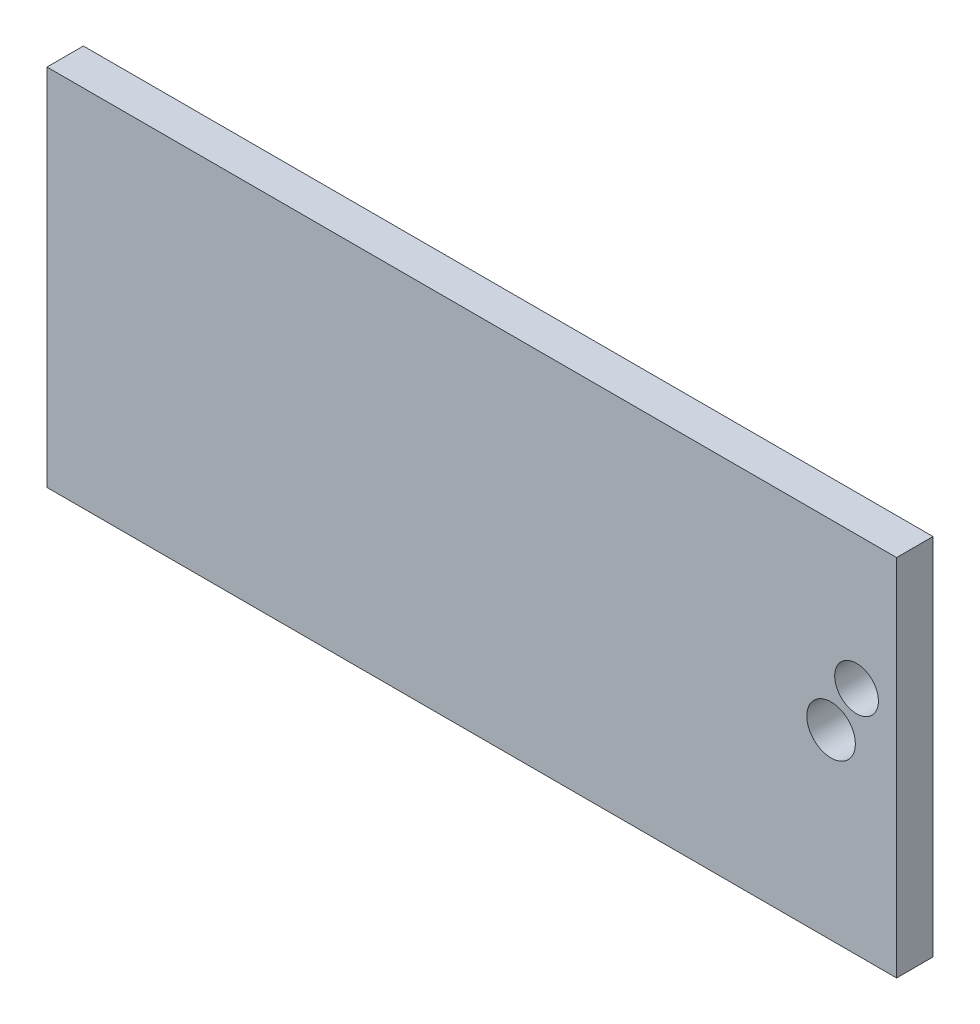
SolidWorks part; units mm, degrees
ref_plane "Plan de face" through (0, 0, 0) normal (0, 0, 1) x (1, 0, 0)
ref_plane "Plan de dessus" through (0, 0, 0) normal (0, 1, 0) x (1, 0, 0)
ref_plane "Plan de droite" through (0, 0, 0) normal (1, 0, 0) x (0, 0, -1)
sketch "Esquisse1" plane through (0, 0, 0) normal (0, 0, 1) x (1, 0, 0)
  line L1 (0, 0) -> (350, 0)
  line L2 (0, 0) -> (0, -150)
  line L3 (0, -150) -> (350, -150)
  line L4 (350, 0) -> (350, -150)
  dimension "D1" = 150
  dimension "D2" = 350
extrude "Boss.-Extru.1" add sketch "Esquisse1" along normal blind 15
sketch "Esquisse2" plane through (0, 0, 0) normal (0, 0, -1) x (-1, 0, 0)
  line L1 (-350, -150) -> (-350, 0) construction
  line L2 (-350, 0) -> (0, 0) construction
  circle A0 centre (-323, -75) radius 10
  dimension "D1" = 20
  dimension "D2" = 27
  dimension "D3" = 75
extrude "Enlèv. mat.-Extru.2" cut sketch "Esquisse2" against normal through all
sketch "Esquisse3" plane through (0, 0, 15) normal (0, 0, 1) x (1, 0, 0)
  circle A0 centre (333.5, -54.9761) radius 9
  dimension "D1" = 18
extrude "Enlèv. mat.-Extru.3" cut sketch "Esquisse3" against normal blind 20
